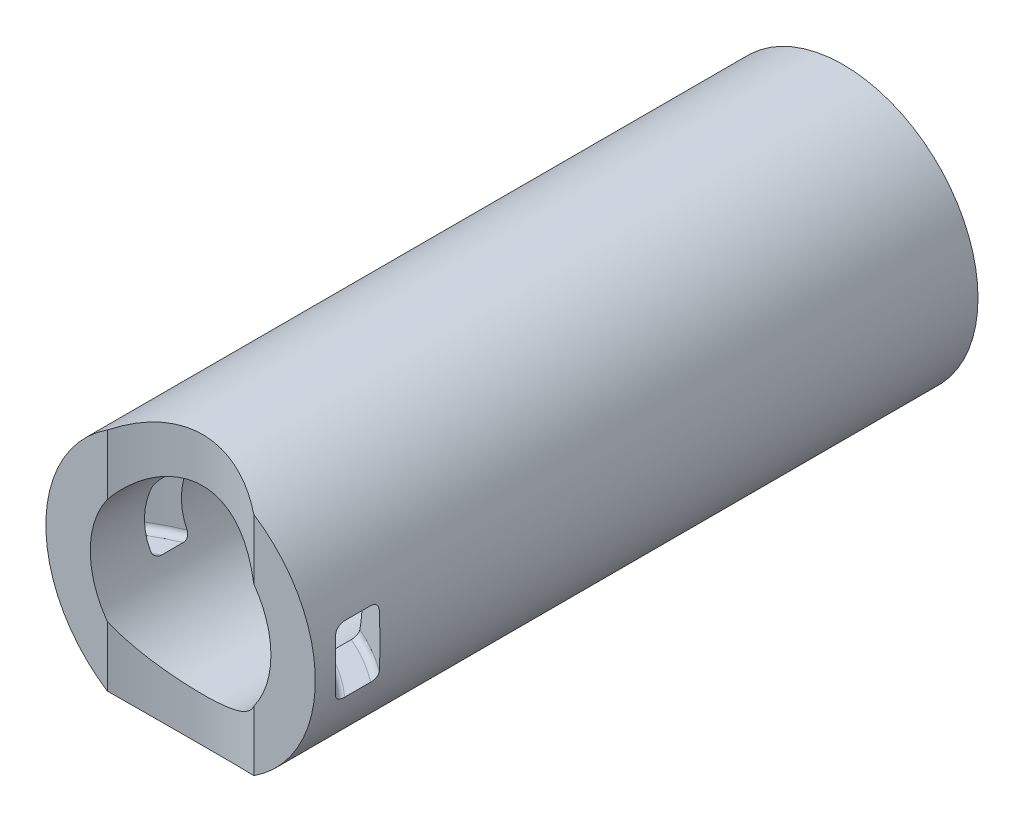
SolidWorks part; units mm, degrees
ref_plane "Front Plane" through (0, 0, 0) normal (0, 0, 1) x (1, 0, 0)
ref_plane "Top Plane" through (0, 0, 0) normal (0, 1, 0) x (1, 0, 0)
ref_plane "Right Plane" through (0, 0, 0) normal (1, 0, 0) x (0, 0, -1)
sketch "Sketch1" plane through (0, 0, 0) normal (0, 0, 1) x (1, 0, 0)
  circle A2 centre (0, 0) radius 6.1
  circle A3 centre (0, 0) radius 1.65
extrude "Boss-Extrude1" add sketch "Sketch1" along normal blind 30
sketch "Sketch2" plane through (0, 0, 0) normal (0, 0, -1) x (-1, 0, 0)
  circle A0 centre (0, 0) radius 3.69
extrude "Cut-Extrude1" cut sketch "Sketch2" against normal blind 4
sketch "Sketch3" plane through (0, 0, 30) normal (0, 0, 1) x (1, 0, 0)
  circle A0 centre (0, 0) radius 4.09
extrude "Cut-Extrude3" cut sketch "Sketch3" against normal offset from surface (22 mm away) 8 up to face at (-3.69, 0, 0)
sketch "Sketch4" plane through (0, 0, 0) normal (0, 1, 0) x (1, 0, 0)
  circle A0 centre (0, -35) radius 6
extrude "Cut-Extrude4" cut sketch "Sketch4" against normal through all both and the other way through all
sketch "Sketch6" plane through (0, 0, 0) normal (1, 0, 0) x (0, 0, -1)
  line L2 (-35, 6.1) -> (-35, -6.1) construction
ref_plane "Plane1" through (0, 0, 35) normal (0, 0, 1) x (1, 0, 0)
sketch "Sketch7" plane through (0, 0, 35) normal (0, 0, 1) x (1, 0, 0)
  line L1 (-9.7, 1.5) -> (-8.8, 1.5)
  line L2 (-10, 1.2) -> (-10, -1.2)
  line L3 (-9.7, -1.5) -> (-8.8, -1.5)
  line L4 (-8.5, 1.2) -> (-8.5, -1.2)
  arc A0 (-8.8, -1.5) -> (-8.5, -1.2) centre (-8.8, -1.2) ccw
  arc A1 (-10, -1.2) -> (-9.7, -1.5) centre (-9.7, -1.2) ccw
  arc A2 (-8.8, 1.5) -> (-8.5, 1.2) centre (-8.8, 1.2) cw
  arc A3 (-9.7, 1.5) -> (-10, 1.2) centre (-9.7, 1.2) ccw
revolve "Cut-Revolve1" cut sketch "Sketch7" angle 360 about L2
